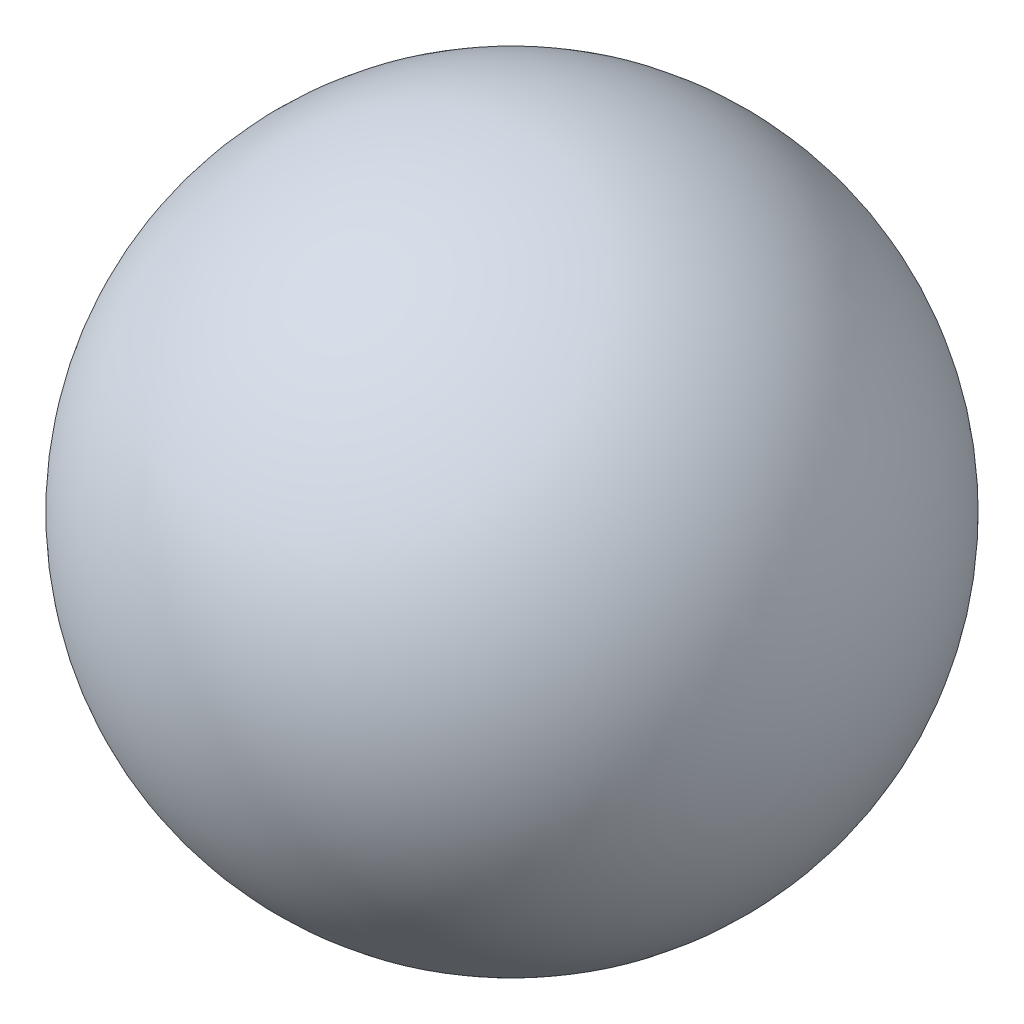
SolidWorks part; units mm, degrees
ref_plane "Plan de face" through (0, 0, 0) normal (0, 0, 1) x (1, 0, 0)
ref_plane "Plan de dessus" through (0, 0, 0) normal (0, 1, 0) x (1, 0, 0)
ref_plane "Plan de droite" through (0, 0, 0) normal (1, 0, 0) x (0, 0, -1)
sketch "Esquisse1" plane through (0, 0, 0) normal (0, 0, 1) x (1, 0, 0)
  line L0 (-23.2493, 2.8442) -> (-23.2493, 42.8442) construction
  arc A0 (-23.2493, 2.8442) -> (-23.2493, 42.8442) centre (-23.2493, 22.8442) ccw
  dimension "D1" = 20
revolve "Révol.-Mince1" add sketch "Esquisse1" angle 360 about L0
